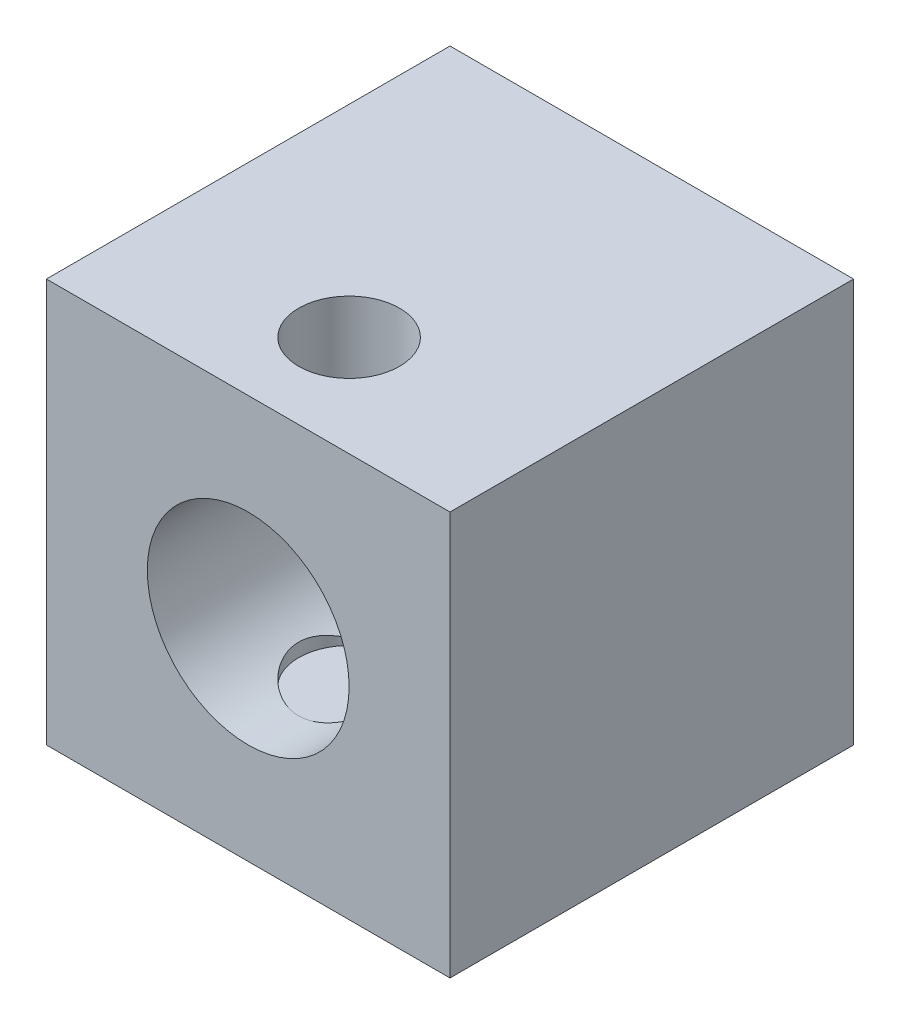
SolidWorks part; units mm, degrees
ref_plane "Plan de face" through (0, 0, 0) normal (0, 0, 1) x (1, 0, 0)
ref_plane "Plan de dessus" through (0, 0, 0) normal (0, 1, 0) x (1, 0, 0)
ref_plane "Plan de droite" through (0, 0, 0) normal (1, 0, 0) x (0, 0, -1)
sketch "Esquisse1" plane through (0, 0, 0) normal (0, 0, 1) x (1, 0, 0)
  line L1 (0, 0) -> (40, 0)
  line L2 (0, 0) -> (0, 40)
  line L3 (0, 40) -> (40, 40)
  line L4 (40, 0) -> (40, 40)
  dimension "D1" = 40
  dimension "D2" = 40
extrude "Boss.-Extru.1" add sketch "Esquisse1" along normal blind 40
sketch "Esquisse2" plane through (0, 0, 40) normal (0, 0, 1) x (1, 0, 0)
  line L0 (0, 40) -> (0, 0) construction
  line L2 (0, 0) -> (40, 0) construction
  circle A0 centre (20, 20) radius 10
  point P4 (0, 0)
  point P6 (19.2209, 0)
  dimension "D1" = 20
  dimension "D2" = 20
extrude "Enlèv. mat.-Extru.1" cut sketch "Esquisse2" against normal blind 40
sketch "Esquisse3" plane through (0, 40, 0) normal (0, 1, 0) x (1, 0, 0)
  line L0 (0, -40) -> (0, 0) construction
  line L1 (40, -40) -> (0, -40) construction
  circle A0 centre (20, -30) radius 5
  dimension "D1" = 20
  dimension "D2" = 10
extrude "Enlèv. mat.-Extru.2" cut sketch "Esquisse3" against normal blind 30
